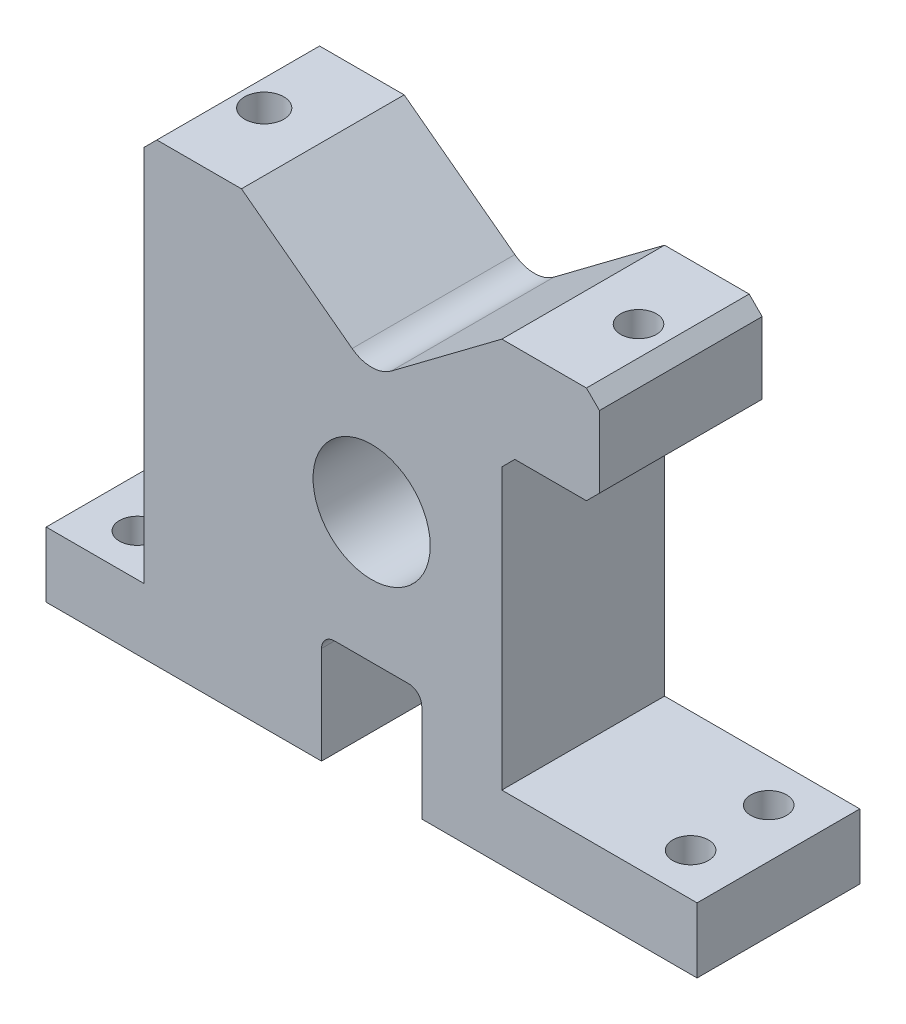
SolidWorks part; units mm, degrees
ref_plane "Front Plane" through (0, 0, 0) normal (0, 0, 1) x (1, 0, 0)
ref_plane "Top Plane" through (0, 0, 0) normal (0, 1, 0) x (1, 0, 0)
ref_plane "Right Plane" through (0, 0, 0) normal (1, 0, 0) x (0, 0, -1)
sketch "Sketch1" plane through (0, 0, 0) normal (0, 0, 1) x (1, 0, 0)
  line L1 (50, 0) -> (50, 10)
  line L2 (50, 10) -> (35, 10)
  line L4 (35, 70) -> (20, 70)
  line L5 (0, 0) -> (0, 37) construction
  line L8 (3, 57.25) -> (20, 70)
  line L9 (-3, 57.25) -> (-20, 70)
  line L10 (-35, 70) -> (-20, 70)
  line L11 (-35, 10) -> (-35, 70)
  line L12 (-50, 10) -> (-35, 10)
  line L13 (-50, 0) -> (-50, 10)
  line L14 (35, 70) -> (35, 55)
  line L16 (-5.7, 17) -> (5.7, 17)
  line L17 (7.7, 15) -> (7.7, 0)
  line L18 (7.7, 0) -> (50, 0)
  line L19 (-7.7, 0) -> (-50, 0)
  line L20 (35, 55) -> (20, 55)
  line L21 (20, 55) -> (20, 10)
  line L22 (20, 10) -> (35, 10)
  line L23 (-7.7, 15) -> (-7.7, 0)
  arc A1 (3, 57.25) -> (-3, 57.25) centre (0, 61.25) cw
  arc A2 (-7.7, 15) -> (-5.7, 17) centre (-5.7, 15) cw
  arc A3 (7.7, 15) -> (5.7, 17) centre (5.7, 15) ccw
  point P17 (0, 55)
  dimension "D1" = 5
  dimension "D2" = 2
  dimension "D3" = 15.4
extrude "Boss-Extrude1" add sketch "Sketch1" along normal blind 25
sketch "Sketch2" plane through (0, 0, 0) normal (0, 0, -1) x (-1, 0, 0)
  circle A0 centre (0, 37) radius 11.2
extrude "Cut-Extrude1" cut sketch "Sketch2" against normal through all
sketch "Sketch4" plane through (0, 10, 0) normal (0, 1, 0) x (1, 0, 0)
  line L0 (-42.5, 0) -> (-42.5, -6.5) construction
  line L3 (-35, 0) -> (-50, 0) construction
  line L4 (-42.5, -25) -> (-42.5, -18.5) construction
  line L5 (-35, -25) -> (-50, -25) construction
  line L6 (42.5, 0) -> (42.5, -6.5) construction
  line L7 (50, 0) -> (35, 0) construction
  line L8 (42.5, -25) -> (42.5, -18.5) construction
sketch "Sketch9" plane through (0, 70, 0) normal (0, 1, 0) x (1, 0, 0)
  line L0 (27.5, -25) -> (27.5, -12.5) construction
  line L1 (35, -25) -> (20, -25) construction
chamfer "Chamfer2" distance 2 angle 45 4 edges at (20, 55, 12.5) (35, 55, 12.5) (35, 70, 12.5) (-35, 70, 12.5)
sketch "Sketch11" plane through (0, 0, 25) normal (0, 0, 1) x (1, 0, 0)
  circle A0 centre (0, 37) radius 11.4
  circle A1 centre (0, 37) radius 9
extrude "Boss-Extrude3" add sketch "Sketch11" against normal blind 18
hole_wizard "M5 Clearance Hole1" positions "Sketch12" profile "Sketch13" hole size "M5" standard "ISO" end condition up to next
sketch "Sketch12" plane through (0, 10, 0) normal (0, 1, 0) x (1, 0, 0)
  point P0 (42.5, -18.5)
  point P3 (42.5, -6.5)
  point P6 (-42.5, -18.5)
  point P9 (-42.5, -6.5)
sketch "Sketch13" plane through (42.5, 10, 18.5) normal (1, 0, 0) x (0, 0, 1)
  line L0 (0, 0) -> (0, 10)
  line L1 (0, 10) -> (2.75, 10)
  line L2 (2.75, 10) -> (2.75, 0)
  line L5 (2.75, 0) -> (0, 0)
  line L11 (0, -6.35) -> (0, 107.95) construction
  dimension "Thru Hole Dia." = 5.5
  dimension "Thru Hole Depth" = 10
sketch "Sketch16" plane through (0, 70, 0) normal (0, 1, 0) x (1, 0, 0)
  line L0 (33, -12.5) -> (28.5, -12.5) construction
  line L1 (33, -25) -> (33, 0) construction
hole_wizard "M5 Clearance Hole2" positions "Sketch17" profile "Sketch18" hole size "M5" standard "ISO"
sketch "Sketch17" plane through (0, 70, 0) normal (0, 1, 0) x (1, 0, 0)
  point P0 (28.5, -12.5)
sketch "Sketch18" plane through (28.5, 70, 12.5) normal (1, 0, 0) x (0, 0, 1)
  line L0 (0, 0) -> (0, 15)
  line L1 (0, 15) -> (2.75, 15)
  line L2 (2.75, 15) -> (2.75, 0)
  line L5 (2.75, 0) -> (0, 0)
  line L11 (0, -6.35) -> (0, 107.95) construction
  dimension "Thru Hole Dia." = 5.5
  dimension "Thru Hole Depth" = 15
sketch "Sketch19" plane through (0, 70, 0) normal (0, 1, 0) x (1, 0, 0)
  line L0 (-33, -25) -> (-33, -12.5) construction
  line L1 (-33, 0) -> (-33, -25) construction
  line L2 (-33, -12.5) -> (-29, -12.5) construction
hole_wizard "Ø6.0mm Dowel Hole1" positions "Sketch20" profile "Sketch21" hole size "Ø6.0" standard "ISO"
sketch "Sketch20" plane through (0, 70, 0) normal (0, 1, 0) x (1, 0, 0)
  point P0 (-29, -12.5)
sketch "Sketch21" plane through (-29, 70, 12.5) normal (1, 0, 0) x (0, 0, 1)
  line L0 (0, 0) -> (0, 41.8026)
  line L1 (0, 41.8026) -> (3, 40)
  line L2 (3, 40) -> (3, 0)
  line L5 (3, 0) -> (0, 0)
  line L10 (0, 41.8026) -> (-3, 40) construction
  line L11 (0, -6.35) -> (0, 107.95) construction
  dimension "Hole Dia." = 6
  dimension "Hole Depth" = 40
  dimension "Drill Angle" = 118
